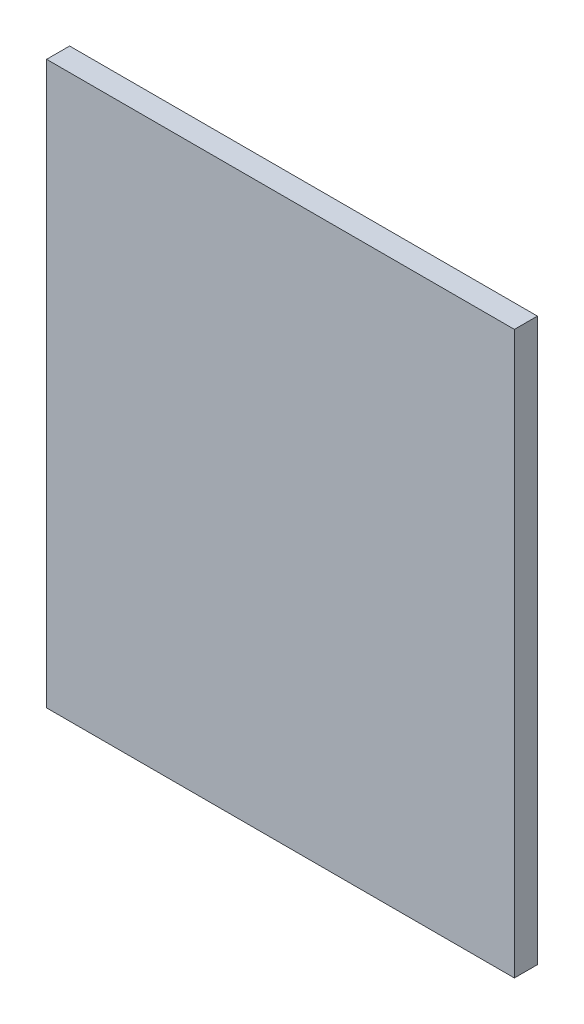
SolidWorks part; units mm, degrees
ref_plane "Plan de face" through (0, 0, 0) normal (0, 0, 1) x (1, 0, 0)
ref_plane "Plan de dessus" through (0, 0, 0) normal (0, 1, 0) x (1, 0, 0)
ref_plane "Plan de droite" through (0, 0, 0) normal (1, 0, 0) x (0, 0, -1)
sketch "Esquisse2" plane through (0, 0, 0) normal (0, 0, 1) x (1, 0, 0)
  line L1 (0, 0) -> (101.6, 0)
  line L2 (0, 0) -> (0, 122)
  line L3 (0, 122) -> (101.6, 122)
  line L4 (101.6, 0) -> (101.6, 122)
  dimension "D1" = 101.6
  dimension "D2" = 122
extrude "Boss.-Extru.1" add sketch "Esquisse2" along normal blind 5
